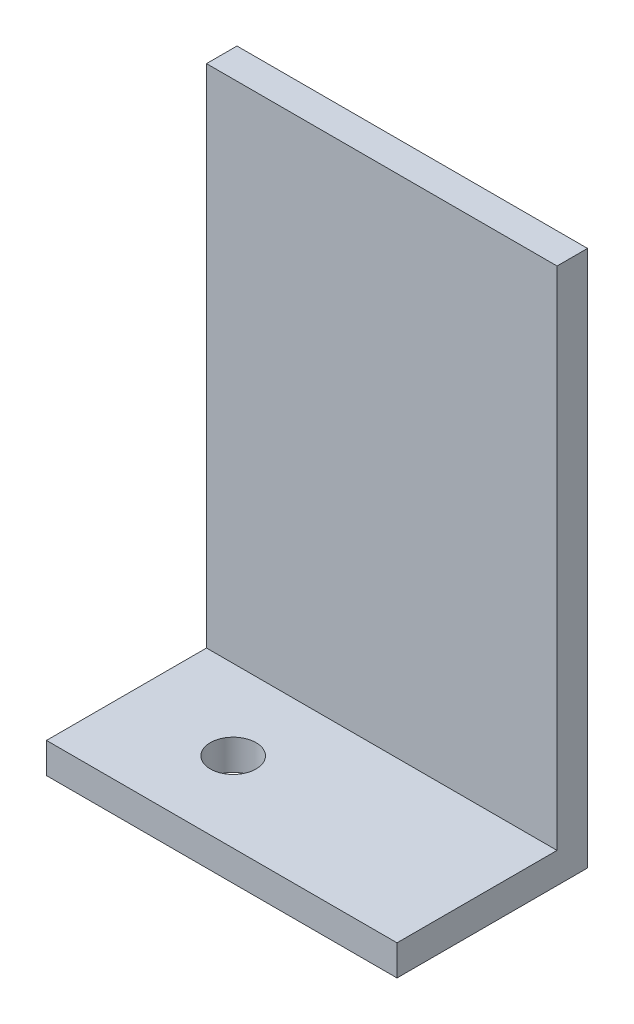
SolidWorks part; units mm, degrees
ref_plane "Front Plane" through (0, 0, 0) normal (0, 0, 1) x (1, 0, 0)
ref_plane "Top Plane" through (0, 0, 0) normal (0, 1, 0) x (1, 0, 0)
ref_plane "Right Plane" through (0, 0, 0) normal (1, 0, 0) x (0, 0, -1)
sketch "Sketch1" plane through (0, 0, 0) normal (0, 1, 0) x (1, 0, 0)
  line L1 (0, 0) -> (23, 0)
  line L2 (0, 0) -> (0, 12.5)
  line L3 (0, 12.5) -> (23, 12.5)
  line L4 (23, 0) -> (23, 12.5)
  dimension "D1" = 12.5
  dimension "D2" = 23
extrude "Boss-Extrude1" add sketch "Sketch1" along normal blind 2
sketch "Sketch2" plane through (0, 0, -12.5) normal (0, 0, -1) x (-1, 0, 0)
  line L1 (-23, 2) -> (0, 2)
  line L2 (-23, 2) -> (-23, 35.2062)
  line L3 (-23, 35.2062) -> (0, 35.2062)
  line L4 (0, 2) -> (0, 35.2062)
extrude "Boss-Extrude2" add sketch "Sketch2" against normal blind 2
sketch "Sketch3" plane through (0, 2, 0) normal (0, 1, 0) x (1, 0, 0)
  line L0 (0, 5.25) -> (23, 5.25) construction
  line L1 (0, 10.5) -> (0, 0) construction
  line L2 (23, 0) -> (23, 10.5) construction
  circle A0 centre (7, 5.25) radius 1.5
  dimension "D1" = 3
  dimension "D2" = 5.5
extrude "Cut-Extrude1" cut sketch "Sketch3" against normal blind 2 contours A0
sketch "Sketch4" plane through (0, 0, -12.5) normal (0, 0, -1) x (-1, 0, 0)
  line L1 (0, 35.2062) -> (0, 0) construction
  line L2 (0, 35.2062) -> (-23, 35.2062) construction
  circle A0 centre (-11, 23.2062) radius 8
  point P2 (-9.8668, 15.3728)
  point P3 (0, 0)
  point P4 (-10.1809, 18.5943)
  point P7 (-11, 20.2323)
  point P8 (0, 0)
  point P9 (-11, 19.1051)
  point P10 (-11, 20.214)
  dimension "D1" = 16
  dimension "D2" = 3
  dimension "D3" = 4
sketch "Sketch5" plane through (0, 0, -12.5) normal (0, 0, -1) x (-1, 0, 0)
sketch "Sketch6" plane through (0, 0, -12.5) normal (0, 0, -1) x (-1, 0, 0)
  line L0 (-23, 35.2062) -> (-23, 0) construction
  line L1 (0, 35.2062) -> (0, 0) construction
  arc A0 (-23, 23.2062) -> (-1.2728, 30.2334) centre (-11, 23.2062) cw
  arc A1 (-1.2728, 30.2334) -> (0, 29.5827) centre (0, 31.1529) ccw
